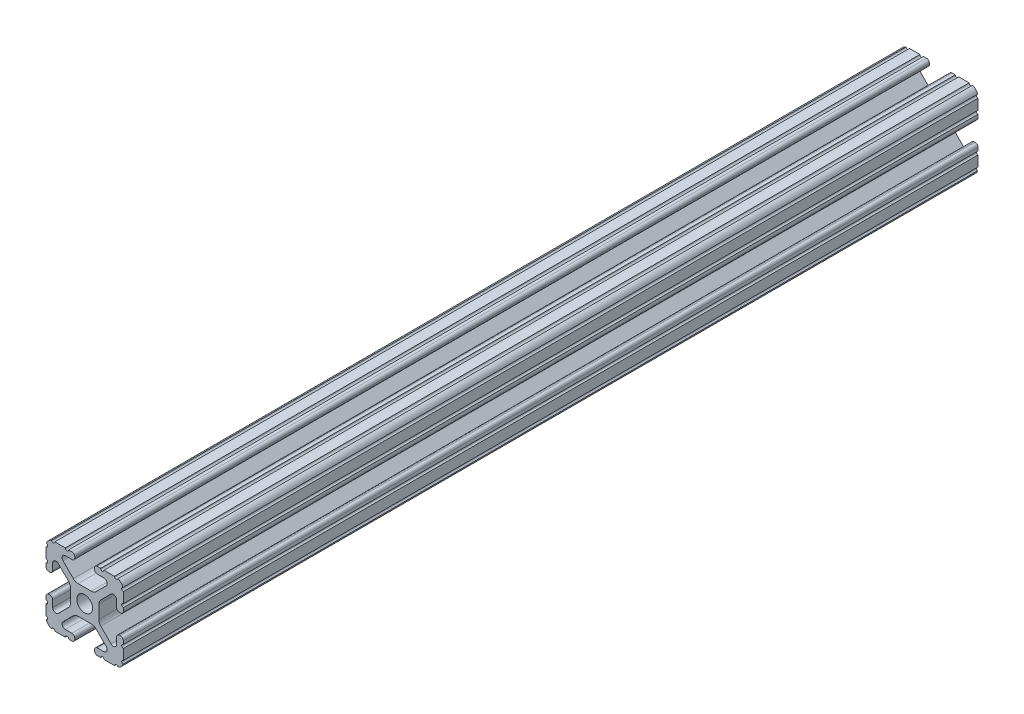
SolidWorks part; units mm, degrees
ref_plane "Front Plane" through (0, 0, 0) normal (0, 0, 1) x (1, 0, 0)
ref_plane "Top Plane" through (0, 0, 0) normal (0, 1, 0) x (1, 0, 0)
ref_plane "Right Plane" through (0, 0, 0) normal (1, 0, 0) x (0, 0, -1)
sketch "Sketch2" plane through (0, 0, 0) normal (0, 0, 1) x (1, 0, 0)
  line L0 (0, 12.7) -> (0, -12.7) construction
  line L1 (-12.7, 0) -> (12.7, 0) construction
  line L2 (3.2512, -12.7) -> (12.7, -12.7)
  line L3 (12.7, -12.7) -> (12.7, -3.2512)
  line L4 (3.2512, -12.7) -> (3.2512, -10.4902)
  line L5 (3.2512, -10.4902) -> (8.9276, -10.4902)
  line L6 (8.9276, -10.4902) -> (3.0856, -4.6482)
  line L7 (0, 0) -> (12.7, -12.7) construction
  line L8 (12.7, -3.2512) -> (10.4902, -3.2512)
  line L9 (10.4902, -3.2512) -> (10.4902, -8.9276)
  line L10 (10.4902, -8.9276) -> (4.6482, -3.0856)
  circle A0 centre (0, 0) radius 2.6035
  arc A1 (6.3485, -10.4902) -> (7.1039, -8.6665) centre (6.3485, -9.4219) ccw construction
  point P8 (0, -4.6482)
  dimension "Center Hole Diameter" = 5.207
  dimension "Rail Height" = 25.4
  dimension "Rail Width" = 25.4
  dimension "T-Slot Width" = 6.5024
  dimension "Slot Inner Width" = 14.8336
  dimension "Thickness" = 2.2098
  dimension "Slot Depth" = 5.842
  dimension "D1" = 2.2098
sketch "Sketch3" plane through (0, 0, 0) normal (1, 0, 0) x (0, 0, -1)
  line L0 (-140.3627, -12.7) -> (140.3627, -12.7) construction
  line L1 (-114.9627, 0) -> (114.9627, 0) construction
  line L2 (140.3627, 0) -> (-140.3627, 0) construction
sketch "Sketch4" plane through (0, 0, 0) normal (0, 0, 1) x (1, 0, 0)
  line L0 (4.1904, -12.7) -> (10.1173, -12.7)
  line L1 (3.2512, -12.7) -> (12.7, -12.7) construction
  line L2 (3.2512, -12.7) -> (3.2512, -10.4902) construction
  line L3 (3.2512, -10.4902) -> (8.9276, -10.4902) construction
  line L4 (3.2512, -11.4294) -> (3.2512, -11.7608)
  line L5 (4.1904, -10.4902) -> (6.3485, -10.4902)
  line L6 (0, -4.6482) -> (2.164, -4.6482)
  line L7 (8.9276, -10.4902) -> (3.0856, -4.6482) construction
  line L8 (3.7373, -5.2999) -> (7.1039, -8.6665)
  line L9 (12.7, -12.7) -> (12.7, -3.2512) construction
  line L10 (10.4902, -8.9276) -> (4.6482, -3.0856) construction
  line L11 (10.4902, -3.2512) -> (10.4902, -8.9276) construction
  line L12 (10.4902, -6.3485) -> (10.4902, -4.1904)
  line L13 (12.7, -3.2512) -> (10.4902, -3.2512) construction
  line L14 (11.4294, -3.2512) -> (11.7608, -3.2512)
  line L15 (12.7, -4.1904) -> (12.7, -10.1173)
  line L16 (8.6665, -7.1039) -> (5.2999, -3.7373)
  line L17 (4.6482, 0) -> (4.6482, -2.164)
  line L18 (-12.7, 0) -> (12.7, 0) construction
  line L19 (0, -4.6482) -> (0, -2.6035)
  line L20 (0, 12.7) -> (0, -12.7) construction
  line L21 (4.6482, 0) -> (2.6035, 0)
  arc A0 (3.2512, -11.7608) -> (4.1904, -12.7) centre (4.1904, -11.7608) ccw
  arc A2 (3.2512, -11.4294) -> (4.1904, -10.4902) centre (4.1904, -11.4294) cw
  arc A3 (6.3485, -10.4902) -> (7.1039, -8.6665) centre (6.3485, -9.4219) ccw
  arc A4 (2.164, -4.6482) -> (3.7373, -5.2999) centre (2.164, -6.8732) cw
  arc A5 (10.1173, -12.7) -> (12.7, -10.1173) centre (10.1173, -10.1173) ccw
  arc A6 (8.6665, -7.1039) -> (10.4902, -6.3485) centre (9.4219, -6.3485) ccw
  arc A7 (10.4902, -4.1904) -> (11.4294, -3.2512) centre (11.4294, -4.1904) cw
  arc A8 (11.7608, -3.2512) -> (12.7, -4.1904) centre (11.7608, -4.1904) cw
  arc A9 (5.2999, -3.7373) -> (4.6482, -2.164) centre (6.8732, -2.164) cw
  circle A10 centre (0, 0) radius 2.6035 construction
  arc A11 (0, -2.6035) -> (2.6035, 0) centre (0, 0) ccw
  dimension "D1" = 2.5827
  dimension "D2" = 2.225
  dimension "D3" = 0.9392
extrude "Boss-Extrude1" add sketch "Sketch4" along normal up to vertex (140.3627 mm away) from vertex at -140.3627 starting at point (0, -12.7, -140.3627)
sketch "Sketch5" plane through (0, 0, 0) normal (0, 0, 1) x (1, 0, 0)
  line L0 (3.2512, -12.7) -> (12.7, -12.7) construction
  line L1 (4.1904, -10.4902) -> (6.3485, -10.4902) construction
  line L3 (0, 0) -> (12.7, -12.7) construction
  line L4 (6.3485, -10.4902) -> (6.3485, -12.7) construction
  line L5 (8.9276, -10.4902) -> (3.0856, -4.6482) construction
  circle A0 centre (10.3562, -12.7) radius 0.5524
  circle A1 centre (5.796, -12.7) radius 0.5524
  circle A2 centre (12.7, -10.3562) radius 0.5524
  circle A3 centre (12.7, -5.796) radius 0.5524
  point P10 (5.2694, -10.4902)
  point P12 (9.4219, -6.3485)
  dimension "D1" = 1.1049
extrude "Cut-Extrude1" cut sketch "Sketch5" against normal through all both and the other way through all
mirror "Mirror1" about plane through (0, 0, 0) normal (1, 0, 0) of bodies 137 134
mirror "Mirror2" about plane through (0, 0, 0) normal (0, 1, 0) of bodies 135
equation "\"D1@Sketch2\"=\"Thickness@Sketch2\""
equation "\"D2@Sketch4\"=\"Slot Inner Width@Sketch2\"*0.15"
equation "\"D1@Sketch4\"=\"D3@Sketch4\"*2.75"
equation "\"D3@Sketch4\"=\"Thickness@Sketch2\"*0.425"
equation "\"D1@Sketch5\"=\"Thickness@Sketch2\"*0.5"
equation "\"D1@Boss-Extrude1\"=\"Length@Sketch3\""
